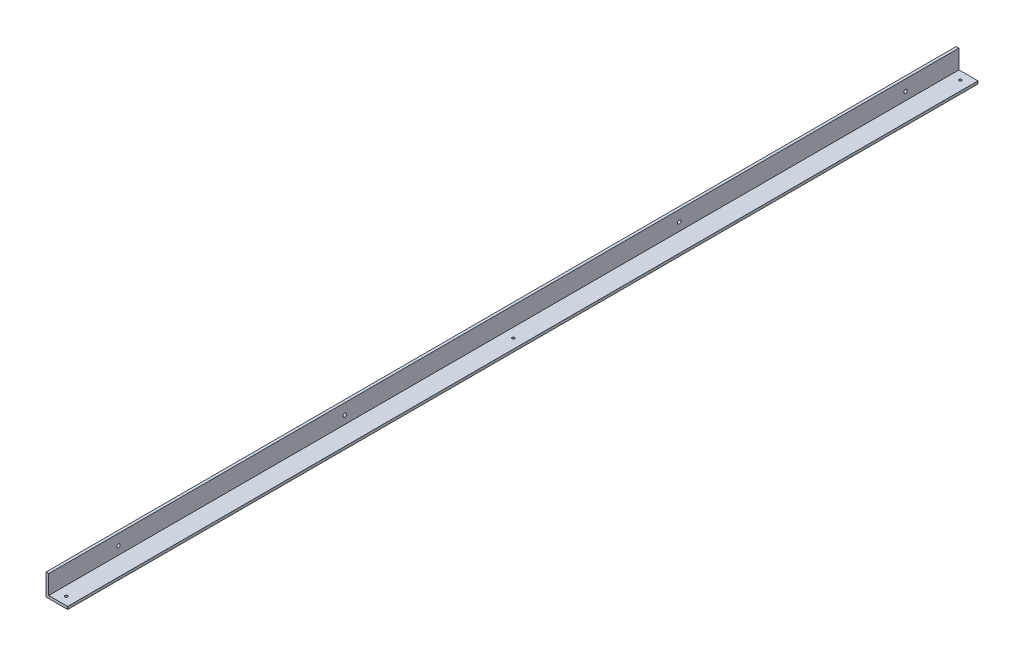
SolidWorks part; units mm, degrees
ref_plane "Alzado" through (0, 0, 0) normal (0, 0, 1) x (1, 0, 0)
ref_plane "Planta" through (0, 0, 0) normal (0, 1, 0) x (1, 0, 0)
ref_plane "Vista lateral" through (0, 0, 0) normal (1, 0, 0) x (0, 0, -1)
sketch "Croquis1" plane through (0, 0, 0) normal (0, 0, 1) x (1, 0, 0)
  line L0 (0, 0) -> (80, 0)
  line L1 (0, 0) -> (0, 80)
  line L2 (0, 80) -> (10, 80)
  line L3 (10, 80) -> (10, 10)
  line L4 (10, 10) -> (80, 10)
  line L5 (80, 10) -> (80, 0)
  dimension "D1" = 80
  dimension "D2" = 80
  dimension "D3" = 10
  dimension "D4" = 10
extrude "Saliente-Extruir1" add sketch "Croquis1" along normal blind 3360
sketch "Croquis2" plane through (0, 0, 0) normal (-1, 0, 0) x (0, 0, 1)
  line L2 (0, 80) -> (0, 0) construction
  circle A0 centre (3102.5, 40) radius 6.35
  circle A3 centre (197.5, 40) radius 6.35
  circle A5 centre (2267.5, 40) radius 6.35
  circle A6 centre (1032.5, 40) radius 6.35
  dimension "D1" = 12.7
  dimension "D2" = 197.5
  dimension "D3" = 835
  dimension "D4" = 12.7
  dimension "D7" = 12.7
  dimension "D8" = 12.7
  dimension "D5" = 1235
  dimension "D6" = 835
extrude "Cortar-Extruir1" cut sketch "Croquis2" against normal up to next
sketch "Croquis3" plane through (0, 10, 0) normal (0, 1, 0) x (1, 0, 0)
  line L0 (80, -3360) -> (10, -3360) construction
  circle A0 centre (45, -3330) radius 4.7625
  circle A1 centre (45, -1680) radius 4.7625
  circle A2 centre (45, -30) radius 4.7625
  dimension "D4" = 9.525
  dimension "D5" = 9.525
  dimension "D6" = 9.525
  dimension "D1" = 30
  dimension "D2" = 3300
  dimension "D3" = 1650
extrude "Cortar-Extruir2" cut sketch "Croquis3" against normal up to next
